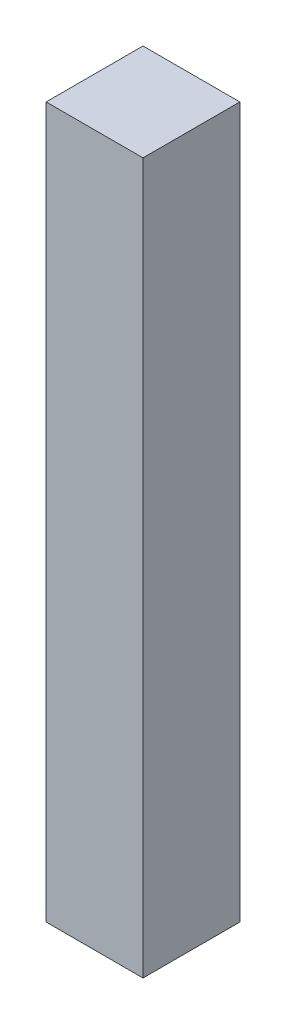
SolidWorks part; units mm, degrees
ref_plane "Front Plane" through (0, 0, 0) normal (0, 0, 1) x (1, 0, 0)
ref_plane "Top Plane" through (0, 0, 0) normal (0, 1, 0) x (1, 0, 0)
ref_plane "Right Plane" through (0, 0, 0) normal (1, 0, 0) x (0, 0, -1)
sketch "Sketch1" plane through (0, 0, 0) normal (0, 1, 0) x (1, 0, 0)
  line L1 (0, 0) -> (15, 0)
  line L2 (0, 0) -> (0, 15)
  line L3 (0, 15) -> (15, 15)
  line L4 (15, 0) -> (15, 15)
  dimension "D1" = 15
extrude "Boss-Extrude1" add sketch "Sketch1" along normal blind 110
